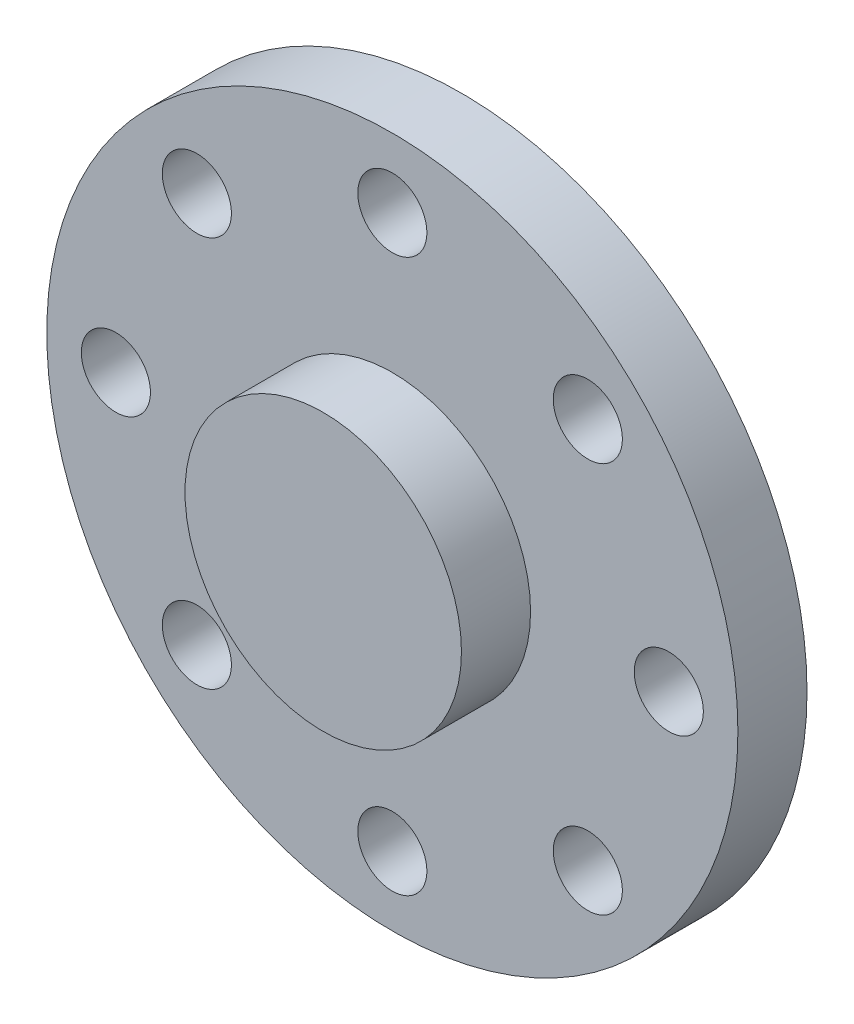
SolidWorks part; units mm, degrees
ref_plane "Plan de face" through (0, 0, 0) normal (0, 0, 1) x (1, 0, 0)
ref_plane "Plan de dessus" through (0, 0, 0) normal (0, 1, 0) x (1, 0, 0)
ref_plane "Plan de droite" through (0, 0, 0) normal (1, 0, 0) x (0, 0, -1)
sketch "Esquisse2" plane through (0, 0, 0) normal (0, 0, 1) x (1, 0, 0)
  line L0 (22.1497, 27.8802) -> (22.1497, 7.8802)
  line L1 (12.1497, 17.8802) -> (32.1497, 17.8802)
  line L2 (29.2207, 24.9512) -> (27.8065, 23.537)
  line L3 (29.2207, 24.9512) -> (15.0786, 10.8091)
  line L4 (15.0786, 24.9512) -> (29.2207, 10.8091)
  line L5 (22.1497, 27.8802) -> (22.1497, 26.4573)
  line L6 (22.1497, 27.8802) -> (22.1497, 25.8802)
  line L7 (15.0786, 24.9512) -> (16.4928, 23.537)
  line L8 (12.1497, 17.8802) -> (14.1497, 17.8802)
  line L9 (15.0786, 10.8091) -> (16.3763, 12.1068)
  line L10 (32.1497, 17.8802) -> (30.1497, 17.8802)
  line L11 (29.2207, 10.8091) -> (27.596, 12.4338)
  line L12 (22.1497, 7.8802) -> (22.1497, 9.6937)
  line L13 (29.2207, 10.8091) -> (27.8065, 12.2233)
  line L14 (22.1497, 7.8802) -> (22.1497, 9.8802)
  line L15 (15.0786, 10.8091) -> (16.6065, 12.337)
  line L16 (15.0786, 10.8091) -> (16.4928, 12.2233)
  line L17 (12.1497, 17.8802) -> (14.1497, 17.8802)
  circle A0 centre (22.1497, 17.8802) radius 10
  circle A1 centre (16.4928, 23.537) radius 1
  circle A2 centre (22.1497, 25.8802) radius 1
  circle A3 centre (27.8065, 23.537) radius 1
  circle A7 centre (30.1497, 17.8802) radius 1
  circle A9 centre (27.8065, 12.2233) radius 1
  circle A10 centre (22.1497, 9.8802) radius 1
  circle A12 centre (16.4928, 12.2233) radius 1
  circle A13 centre (14.1497, 17.8802) radius 1
  point P31 (0, 0)
extrude "Boss.-Extru.1" add sketch "Esquisse2" along normal blind 2
sketch "Esquisse3" plane through (0, 0, 2) normal (0, 0, 1) x (1, 0, 0)
  line L0 (22.1497, 27.8802) -> (22.1497, 7.8802)
  circle A0 centre (22.1497, 17.8802) radius 10 construction
  circle A1 centre (22.1497, 17.8802) radius 4
extrude "Boss.-Extru.2" add sketch "Esquisse3" along normal blind 2 contours L0 A1 | L0 A1
